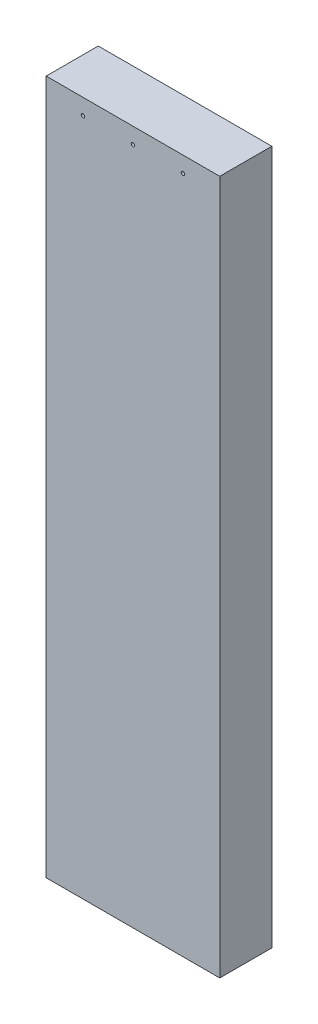
SolidWorks part; units mm, degrees
ref_plane "Front Plane" through (0, 0, 0) normal (0, 0, 1) x (1, 0, 0)
ref_plane "Top Plane" through (0, 0, 0) normal (0, 1, 0) x (1, 0, 0)
ref_plane "Right Plane" through (0, 0, 0) normal (1, 0, 0) x (0, 0, -1)
sketch "Sketch1" plane through (0, 0, 0) normal (0, 1, 0) x (1, 0, 0)
  line L1 (0, 0) -> (63.5, 0)
  line L2 (0, 0) -> (0, 19.05)
  line L3 (0, 19.05) -> (63.5, 19.05)
  line L4 (63.5, 0) -> (63.5, 19.05)
  dimension "D1" = 19.05
  dimension "D2" = 63.5
extrude "Boss-Extrude1" add sketch "Sketch1" along normal blind 254
sketch "Sketch2" plane through (0, 0, 0) normal (0, 0, 1) x (1, 0, 0)
  line L0 (13.462, 248.158) -> (50.038, 248.158) construction
  line L1 (0, 254) -> (63.5, 254) construction
  line L2 (31.75, 254) -> (31.75, 226.7643) construction
  circle A0 centre (13.462, 248.158) radius 0.635
  circle A1 centre (31.75, 248.158) radius 0.635
  circle A2 centre (50.038, 248.158) radius 0.635
  point P6 (31.75, 248.158)
  dimension "D3" = 1.27
  dimension "D1" = 5.842
  dimension "D2" = 36.576
extrude "Cut-Extrude1" cut sketch "Sketch2" against normal through all
